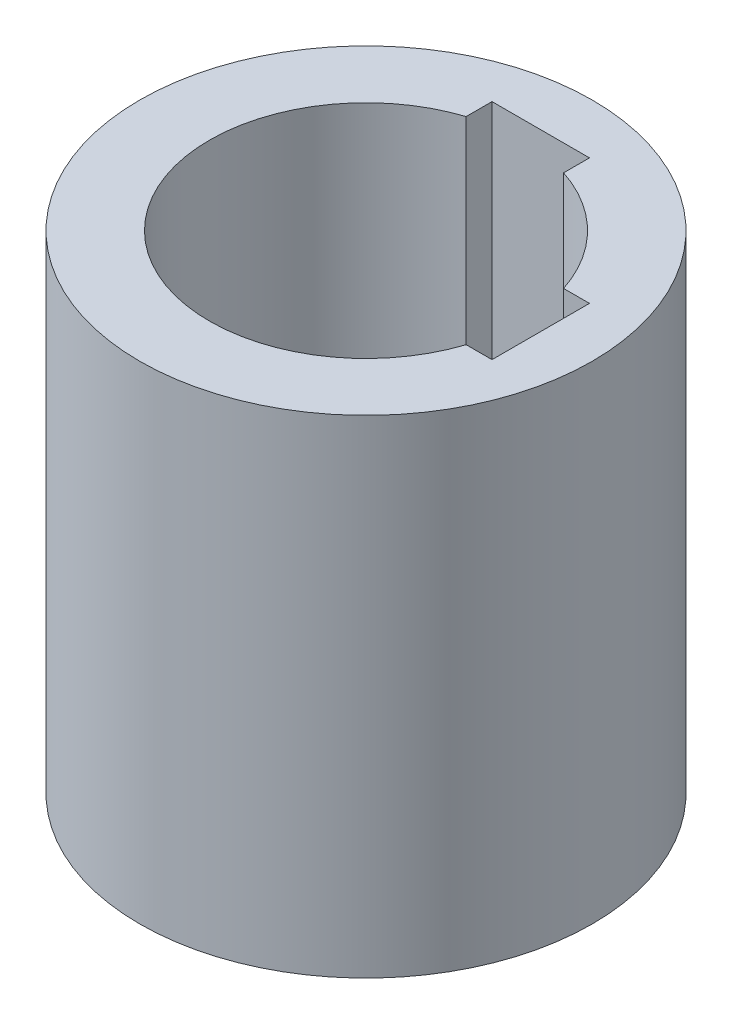
SolidWorks part; units mm, degrees
ref_plane "Front Plane" through (0, 0, 0) normal (0, 0, 1) x (1, 0, 0)
ref_plane "Top Plane" through (0, 0, 0) normal (0, 1, 0) x (1, 0, 0)
ref_plane "Right Plane" through (0, 0, 0) normal (1, 0, 0) x (0, 0, -1)
sketch "Sketch1" plane through (0, 0, 0) normal (0, 1, 0) x (1, 0, 0)
  circle A0 centre (0, 0) radius 22.5
  circle A1 centre (0, 0) radius 32.5
  dimension "D1" = 45
  dimension "D2" = 65
extrude "Boss-Extrude1" add sketch "Sketch1" along normal mid plane 70
sketch "Sketch2" plane through (0, 35, 0) normal (0, 1, 0) x (1, 0, 0)
  line L0 (0, 0) -> (44.5808, 0) construction
  line L2 (25.1, -7) -> (18.1, -7)
  line L3 (25.1, -7) -> (25.1, 7)
  line L4 (25.1, 7) -> (18.1, 7)
  line L5 (18.1, -7) -> (18.1, 7)
  line L6 (25.1, -7) -> (18.1, 7) construction
  line L7 (25.1, 7) -> (18.1, -7) construction
  point P3 (21.6, 0)
  dimension "D1" = 25.1
  dimension "D2" = 14
  dimension "D3" = 7
extrude "Cut-Extrude1" cut sketch "Sketch2" against normal through all
pattern_circular "CirPattern1" count 2 every 90 about axis through (0, 0, 0) along (0, 1, 0) of "Cut-Extrude1"
